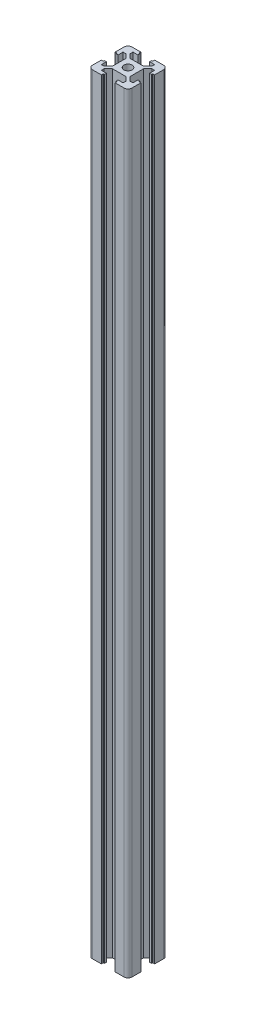
SolidWorks part; units mm, degrees
ref_plane "Спереди" through (0, 0, 0) normal (0, 0, 1) x (1, 0, 0)
ref_plane "Сверху" through (0, 0, 0) normal (0, 1, 0) x (1, 0, 0)
ref_plane "Справа" through (0, 0, 0) normal (1, 0, 0) x (0, 0, -1)
other "Configuration Table"
sketch "Эскиз3" plane through (0, 0, 0) normal (0, 1, 0) x (1, 0, 0)
  line L0 (0, 10) -> (0, 4.5) construction
  line L1 (-10, -10) -> (-3.5, -10)
  line L2 (-10, -10) -> (-10, -3.5)
  line L3 (-10, 10) -> (-3.5, 10)
  line L4 (10, -10) -> (10, -3.5)
  line L5 (-10, -10) -> (10, 10) construction
  line L6 (-10, 10) -> (10, -10) construction
  line L7 (-3.5, 10) -> (-3.5, 9)
  line L8 (-3.5, 9) -> (-3, 9)
  line L9 (-3, 9) -> (-3, 8)
  line L10 (-3, 8) -> (-5.5, 8)
  line L11 (-5.5, 8) -> (-5.5, 6.5607)
  line L12 (-5.5, 6.5607) -> (-3.4393, 4.5)
  line L13 (5.5, 8) -> (5.5, 6.5607)
  line L14 (-3.4393, -4.5) -> (3.4393, -4.5)
  line L15 (-4.5, -3.4393) -> (-4.5, 3.4393)
  line L16 (-3.4393, 4.5) -> (3.4393, 4.5)
  line L17 (4.5, -3.4393) -> (4.5, 3.4393)
  line L20 (5.5, 6.5607) -> (3.4393, 4.5)
  line L21 (3, 8) -> (5.5, 8)
  line L22 (3, 9) -> (3, 8)
  line L23 (3.5, 9) -> (3, 9)
  line L24 (3.5, 10) -> (3.5, 9)
  line L25 (3.5, 10) -> (10, 10)
  line L26 (-3.5, 10) -> (3.5, 10) construction
  line L27 (-6.5607, 5.5) -> (-4.5, 3.4393)
  line L28 (-8, 5.5) -> (-6.5607, 5.5)
  line L29 (-8, 3) -> (-8, 5.5)
  line L30 (-9, 3) -> (-8, 3)
  line L31 (-9, 3.5) -> (-9, 3)
  line L32 (-10, 3.5) -> (-9, 3.5)
  line L33 (10, 3.5) -> (9, 3.5)
  line L34 (6.5607, 5.5) -> (4.5, 3.4393)
  line L35 (9, 3.5) -> (9, 3)
  line L36 (9, 3) -> (8, 3)
  line L37 (8, 3) -> (8, 5.5)
  line L38 (8, 5.5) -> (6.5607, 5.5)
  line L39 (0, 0) -> (-10, 0) construction
  line L40 (-9, -3.5) -> (-9, -3)
  line L41 (-10, -3.5) -> (-9, -3.5)
  line L42 (-9, -3) -> (-8, -3)
  line L43 (-8, -3) -> (-8, -5.5)
  line L44 (-8, -5.5) -> (-6.5607, -5.5)
  line L45 (-6.5607, -5.5) -> (-4.5, -3.4393)
  line L46 (9, -3.5) -> (9, -3)
  line L47 (10, -3.5) -> (9, -3.5)
  line L48 (9, -3) -> (8, -3)
  line L49 (8, -3) -> (8, -5.5)
  line L50 (8, -5.5) -> (6.5607, -5.5)
  line L51 (6.5607, -5.5) -> (4.5, -3.4393)
  line L52 (3.5, -10) -> (3.5, -9)
  line L53 (3.5, -9) -> (3, -9)
  line L54 (3, -9) -> (3, -8)
  line L55 (3, -8) -> (5.5, -8)
  line L56 (5.5, -8) -> (5.5, -6.5607)
  line L57 (5.5, -6.5607) -> (3.4393, -4.5)
  line L58 (-5.5, -6.5607) -> (-3.4393, -4.5)
  line L59 (-5.5, -8) -> (-5.5, -6.5607)
  line L60 (-3, -8) -> (-5.5, -8)
  line L61 (-3, -9) -> (-3, -8)
  line L62 (-3.5, -9) -> (-3, -9)
  line L63 (-3.5, -10) -> (-3.5, -9)
  line L64 (0, 0) -> (0, -10) construction
  line L65 (4.5, 0) -> (10, 0) construction
  line L66 (3.5, -10) -> (10, -10)
  line L67 (-10, 3.5) -> (-10, 10)
  line L68 (10, 3.5) -> (10, 10)
  line L69 (-10, 3.5) -> (-10, -3.5) construction
  line L70 (10, 3.5) -> (10, -3.5) construction
  line L71 (-3.5, -10) -> (3.5, -10) construction
  point P0 (0, 0)
  point P14 (0, 0)
  dimension "D1" = 20
  dimension "D2" = 20
  dimension "D3" = 6.8787
  dimension "D4" = 0.75
  dimension "D5" = 5.5
  dimension "D6" = 3.5
  dimension "D7" = 3
  dimension "D8" = 1
  dimension "D9" = 1
  dimension "D10" = 1
  dimension "D11" = 90
extrude "Бобышка-Вытянуть1" add sketch "Эскиз3" along normal blind 390
fillet "Скругление1" radius 2 4 edges at (10, 195, -10) (10, 195, 10) (-10, 195, 10) (-10, 195, -10)
fillet "Скругление2" radius 0.2 8 edges at (3.5, 195, 9) (-3.5, 195, 9) (-9, 195, 3.5) (-9, 195, -3.5) (9, 195, 3.5) (9, 195, -3.5) (-3.5, 195, -9) (3.5, 195, -9)
sketch "Эскиз4" plane through (0, 390, 0) normal (0, 1, 0) x (1, 0, 0)
  circle A0 centre (0, 0) radius 2.1
  dimension "D1" = 4.2
extrude "Вырез-Вытянуть1" cut sketch "Эскиз4" against normal through all
